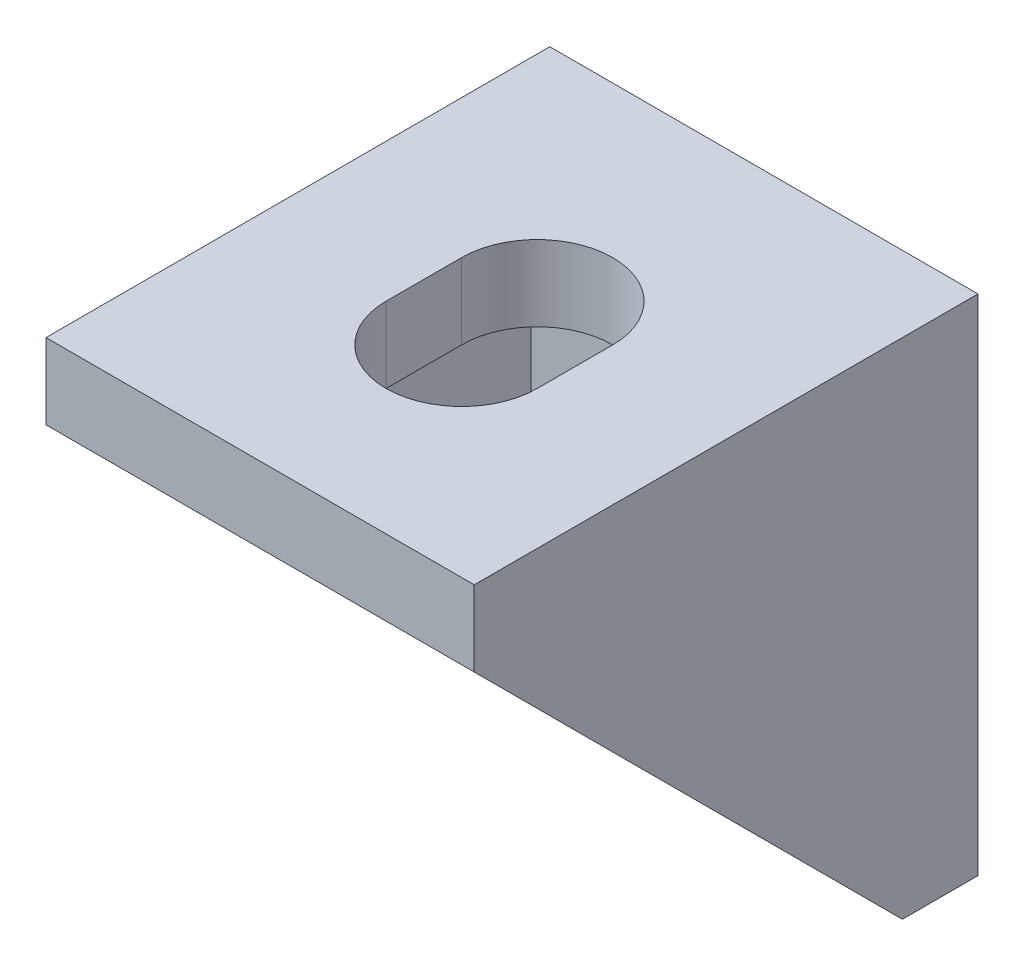
SolidWorks part; units mm, degrees
ref_plane "Спереди" through (0, 0, 0) normal (0, 0, 1) x (1, 0, 0)
ref_plane "Сверху" through (0, 0, 0) normal (0, 1, 0) x (1, 0, 0)
ref_plane "Справа" through (0, 0, 0) normal (1, 0, 0) x (0, 0, -1)
sketch "Эскиз1" plane through (0, 0, 0) normal (0, 0, 1) x (1, 0, 0)
  line L3 (-20.775, 21.5115) -> (-20.775, -19.7929) construction
  line L4 (-29.275, 5.6854) -> (-12.275, 5.6854)
  line L5 (-29.275, 5.6854) -> (-29.275, -14.3146)
  line L6 (-29.275, -14.3146) -> (-12.275, -14.3146)
  line L7 (-12.275, 5.6854) -> (-12.275, -14.3146)
  line L8 (-20.775, -3.3146) -> (-20.775, -6.3146) construction
  line L9 (-17.775, -3.3146) -> (-17.775, -6.3146)
  line L10 (-23.775, -3.3146) -> (-23.775, -6.3146)
  arc A0 (-17.775, -3.3146) -> (-23.775, -3.3146) centre (-20.775, -3.3146) ccw
  arc A1 (-23.775, -6.3146) -> (-17.775, -6.3146) centre (-20.775, -6.3146) ccw
  point P8 (-20.775, -4.8146)
  dimension "D3" = 3
  dimension "D4" = 9
  dimension "D5" = 8
  dimension "D1" = 17
  dimension "D2" = 20
  dimension "D6" = 8.5
extrude "Бобышка-Вытянуть1" add sketch "Эскиз1" along normal blind 3
sketch "Эскиз2" plane through (0, 0, 3) normal (0, 0, 1) x (1, 0, 0)
  line L0 (-29.275, 5.6854) -> (-29.275, -14.3146) construction
  line L1 (-12.275, 5.6854) -> (-29.275, 5.6854)
  line L2 (-12.275, 5.6854) -> (-12.275, 2.6854)
  line L3 (-12.275, 2.6854) -> (-29.275, 2.6854)
  line L4 (-29.275, 5.6854) -> (-29.275, 2.6854)
  dimension "D1" = 3
extrude "Бобышка-Вытянуть2" add sketch "Эскиз2" along normal blind 17
sketch "Эскиз3" plane through (0, 2.6854, 0) normal (0, -1, 0) x (1, 0, 0)
  line L0 (-20.775, 25.8712) -> (-20.775, -7.8712) construction
  line L1 (-20.775, 12) -> (-20.775, 9) construction
  line L2 (-17.775, 12) -> (-17.775, 9)
  line L3 (-23.775, 12) -> (-23.775, 9)
  line L4 (-29.275, 20) -> (-12.275, 20) construction
  arc A0 (-17.775, 12) -> (-23.775, 12) centre (-20.775, 12) ccw
  arc A1 (-23.775, 9) -> (-17.775, 9) centre (-20.775, 9) ccw
  point P4 (-20.775, 10.5)
  dimension "D1" = 8
extrude "Вырез-Вытянуть1" cut sketch "Эскиз3" against normal blind 17
sketch "Эскиз4" plane through (-29.275, 0, 0) normal (-1, 0, 0) x (0, 0, 1)
  line L0 (20, 2.6854) -> (3, 2.6854)
  line L1 (3, 2.6854) -> (3, -14.3146)
  line L2 (3, -14.3146) -> (20, 2.6854)
extrude "Бобышка-Вытянуть3" add sketch "Эскиз4" against normal blind 2.25
sketch "Эскиз5" plane through (-12.275, 0, 0) normal (1, 0, 0) x (0, 0, -1)
  line L0 (-3, -14.3146) -> (-3, 2.6854)
  line L1 (-3, 2.6854) -> (-20, 2.6854)
  line L2 (-20, 2.6854) -> (-3, -14.3146)
extrude "Бобышка-Вытянуть4" add sketch "Эскиз5" against normal blind 2.25
